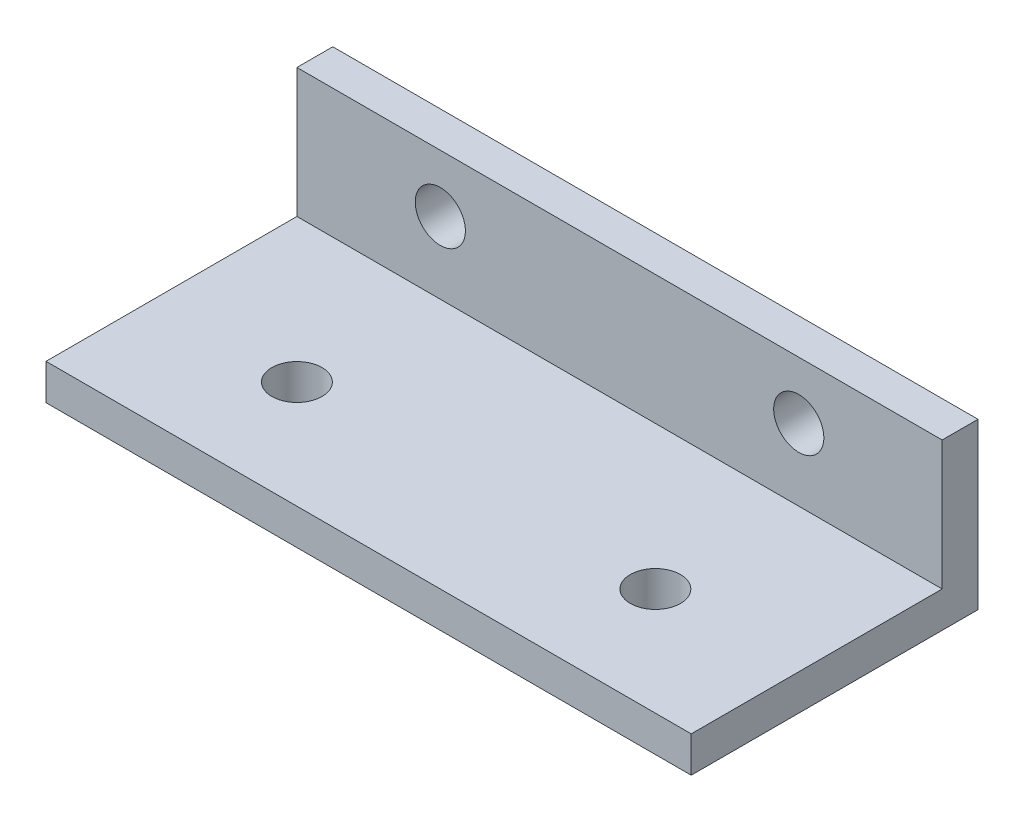
SolidWorks part; units mm, degrees
material "1060 Alloy"
ref_plane "Plano frontal" through (0, 0, 0) normal (0, 0, 1) x (1, 0, 0)
ref_plane "Plano superior" through (0, 0, 0) normal (0, 1, 0) x (1, 0, 0)
ref_plane "Plano direito" through (0, 0, 0) normal (1, 0, 0) x (0, 0, -1)
sketch "Sketch2" plane through (0, 0, 0) normal (0, 0, 1) x (1, 0, 0)
  line L0 (45, 0) -> (-45, 0)
  line L1 (-45, 0) -> (-45, -23)
  line L2 (0, -55) -> (0, 55) construction
  line L3 (45, 0) -> (45, -23)
  line L4 (-45, -23) -> (45, -23)
  point P6 (0, 0)
  dimension "D1" = 90
  dimension "D2" = 23
extrude "Boss-Extrude2" add sketch "Sketch2" along normal blind 5
sketch "Sketch4" plane through (0, 0, 5) normal (0, 0, 1) x (1, 0, 0)
  line L0 (-45, -18) -> (45, -18)
  line L1 (-45, 0) -> (-45, -23) construction
  line L2 (45, -23) -> (45, 0) construction
  line L3 (45, -18) -> (45, -23)
  line L4 (45, -23) -> (-45, -23)
  line L5 (-45, -23) -> (-45, -18)
  dimension "D1" = 5
extrude "Boss-Extrude3" add sketch "Sketch4" along normal blind 35
hole_wizard "M8x1.0 Tapped Hole1" positions "Sketch5" profile "Sketch6" tap size "M8x1.0" standard "ISO" end condition through all
sketch "Sketch5" plane through (0, 0, 5) normal (0, 0, 1) x (1, 0, 0)
  line L0 (45, -18) -> (-45, -18) construction
  line L1 (45, -18) -> (-45, -18) construction
  line L2 (45, -18) -> (45, 0) construction
  point P0 (-25, -8)
  point P2 (25, -8)
  dimension "D1" = 10
  dimension "D2" = 50
  dimension "D3" = 10
  dimension "D4" = 20
sketch "Sketch6" plane through (-25, -8, 5) normal (1, 0, 0) x (0, -1, 0)
  line L0 (0, 0) -> (0, 5)
  line L1 (0, 5) -> (3.5, 5)
  line L2 (3.5, 5) -> (3.5, 0)
  line L5 (3.5, 0) -> (0, 0)
  line L11 (0, -6.35) -> (0, 107.95) construction
  dimension "Thru Tap Drill Dia." = 7
  dimension "Thru Tap Drill Depth" = 5
cosmetic thread "Hole Thread5" parameters "D2"=8
cosmetic thread "Hole Thread6" parameters "D2"=8
hole_wizard "M8x1.0 Tapped Hole2" positions "Sketch7" profile "Sketch8" tap size "M8x1.0" standard "ISO" end condition through all
sketch "Sketch7" plane through (0, -18, 0) normal (0, 1, 0) x (1, 0, 0)
  line L0 (45, -5) -> (-45, -5) construction
  line L1 (45, -40) -> (45, -5) construction
  point P0 (-25, -25)
  point P2 (25, -25)
  dimension "D1" = 50
  dimension "D2" = 20
  dimension "D3" = 20
sketch "Sketch8" plane through (-25, -18, 25) normal (1, 0, 0) x (0, 0, 1)
  line L0 (0, 0) -> (0, 5)
  line L1 (0, 5) -> (3.5, 5)
  line L2 (3.5, 5) -> (3.5, 0)
  line L5 (3.5, 0) -> (0, 0)
  line L11 (0, -6.35) -> (0, 107.95) construction
  dimension "Thru Tap Drill Dia." = 7
  dimension "Thru Tap Drill Depth" = 5
cosmetic thread "Hole Thread3" parameters "D2"=8
cosmetic thread "Hole Thread4" parameters "D2"=8
